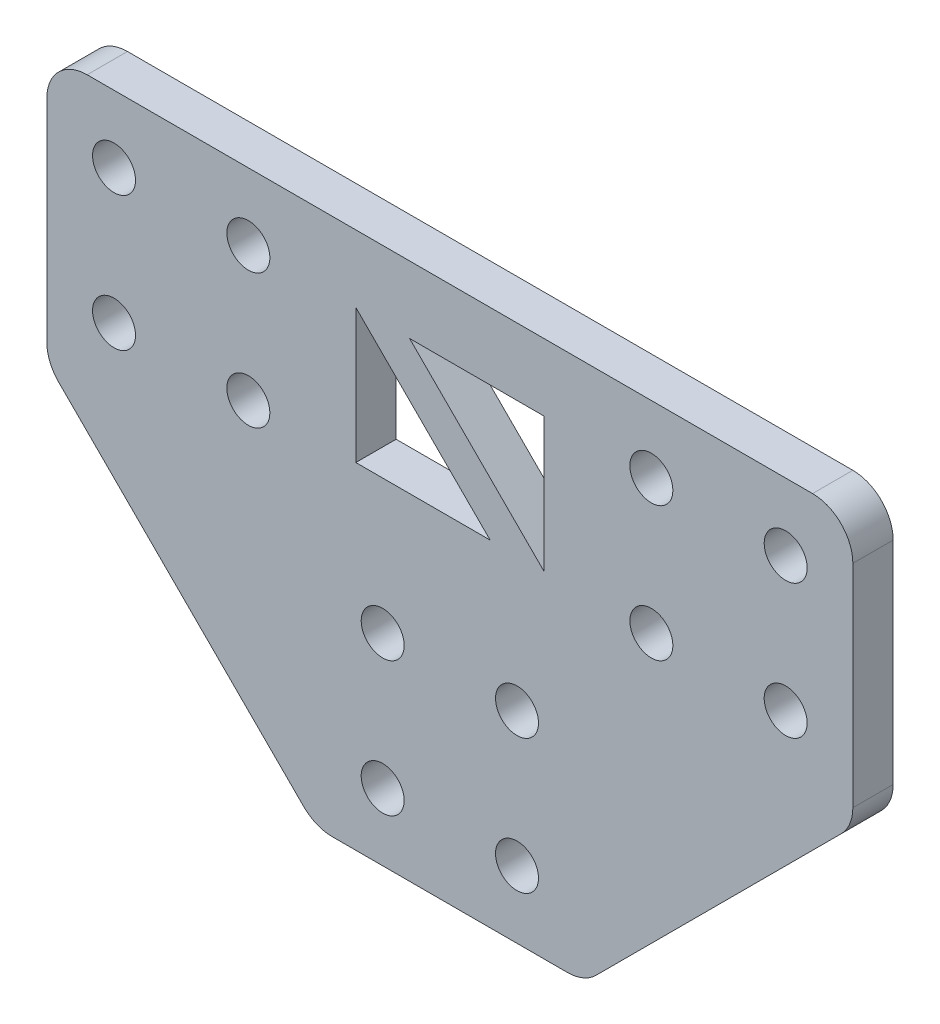
SolidWorks part; units mm, degrees
ref_plane "前视基准面" through (0, 0, 0) normal (0, 0, 1) x (1, 0, 0)
ref_plane "上视基准面" through (0, 0, 0) normal (0, 1, 0) x (1, 0, 0)
ref_plane "右视基准面" through (0, 0, 0) normal (1, 0, 0) x (0, 0, -1)
other "Configuration Table"
sketch "草图1" plane through (0, 0, 0) normal (0, 0, 1) x (1, 0, 0)
  line L0 (0, 0) -> (60, 0)
  line L1 (60, 0) -> (60, -20)
  line L2 (60, -20) -> (40, -40)
  line L3 (40, -40) -> (20, -40)
  line L4 (20, -40) -> (0, -20)
  line L5 (0, -20) -> (0, 0)
  line L6 (30, 0) -> (30, -40) construction
  line L7 (0, -10) -> (30, -10) construction
  line L8 (10, -10) -> (10, 0) construction
  line L9 (30, -30) -> (10, -30) construction
  line L10 (23, -5) -> (23, -15)
  line L11 (23, -15) -> (33, -15)
  line L12 (33, -15) -> (23, -5)
  line L13 (27, -5) -> (37, -5)
  line L14 (37, -5) -> (37, -15)
  line L15 (37, -15) -> (27, -5)
  circle A0 centre (5, -5) radius 1.6
  circle A1 centre (15, -5) radius 1.6
  circle A2 centre (15, -15) radius 1.6
  circle A3 centre (5, -15) radius 1.6
  circle A4 centre (55, -15) radius 1.6
  circle A5 centre (45, -15) radius 1.6
  circle A6 centre (45, -5) radius 1.6
  circle A7 centre (55, -5) radius 1.6
  circle A8 centre (25, -35) radius 1.6
  circle A9 centre (35, -35) radius 1.6
  circle A10 centre (35, -25) radius 1.6
  circle A11 centre (25, -25) radius 1.6
  point P45 (31.9028, -15)
  point P46 (33, -15)
  point P47 (0, 0)
  dimension "D8" = 3.2
  dimension "D11" = 3.2
  dimension "D1" = 20
  dimension "D2" = 20
  dimension "D3" = 20
  dimension "D4" = 60
  dimension "D5" = 40
  dimension "D6" = 10
  dimension "D7" = 10
  dimension "D9" = 5
  dimension "D10" = 5
  dimension "D12" = 5
  dimension "D13" = 5
  dimension "D14" = 10
  dimension "D15" = 10
  dimension "D16" = 10
  dimension "D17" = 10
  dimension "D18" = 7
  dimension "D19" = 7
extrude "凸台-拉伸1" add sketch "草图1" along normal blind 3
fillet "圆角1" radius 3 6 edges at (60, -20, 1.5) (0, -20, 1.5) (20, -40, 1.5) (40, -40, 1.5) (60, 0, 1.5) (0, 0, 1.5)
